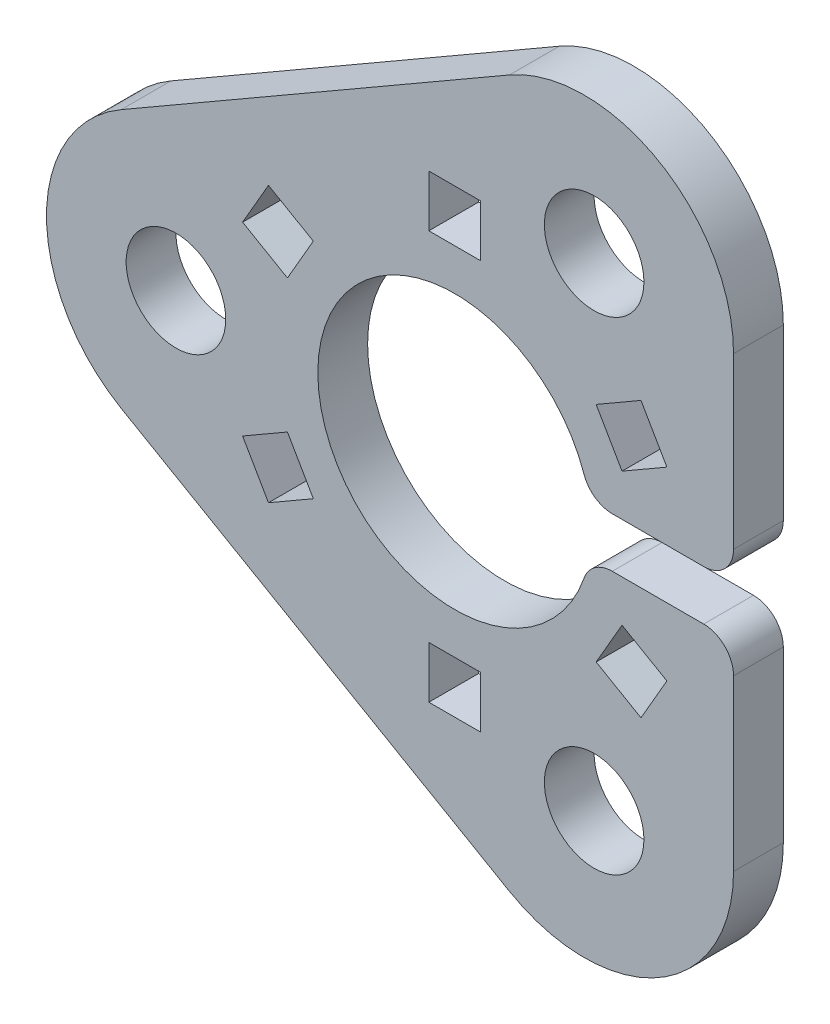
SolidWorks part; units mm, degrees
ref_plane "Front Plane" through (0, 0, 0) normal (0, 0, 1) x (1, 0, 0)
ref_plane "Top Plane" through (0, 0, 0) normal (0, 1, 0) x (1, 0, 0)
ref_plane "Right Plane" through (0, 0, 0) normal (1, 0, 0) x (0, 0, -1)
sketch "Sketch1" plane through (0, 0, 0) normal (0, 0, 1) x (1, 0, 0)
  line L0 (-26, 0) -> (26, 0) construction
  line L7 (-2.6, 23.1) -> (2.6, 23.1)
  line L8 (-2.6, 23.1) -> (-2.6, 17.9)
  line L9 (-2.6, 17.9) -> (2.6, 17.9)
  line L10 (2.6, 23.1) -> (2.6, 17.9)
  line L23 (0, 26) -> (0, -26) construction
  line L24 (21.3052, 9.2983) -> (16.8019, 6.6983)
  line L25 (14.2019, 11.2017) -> (16.8019, 6.6983)
  line L26 (18.7052, 13.8017) -> (14.2019, 11.2017)
  line L27 (18.7052, 13.8017) -> (21.3052, 9.2983)
  line L28 (18.7052, -13.8017) -> (14.2019, -11.2017)
  line L29 (16.8019, -6.6983) -> (14.2019, -11.2017)
  line L30 (21.3052, -9.2983) -> (16.8019, -6.6983)
  line L31 (21.3052, -9.2983) -> (18.7052, -13.8017)
  line L32 (-2.6, -23.1) -> (-2.6, -17.9)
  line L33 (2.6, -17.9) -> (-2.6, -17.9)
  line L34 (2.6, -23.1) -> (2.6, -17.9)
  line L35 (2.6, -23.1) -> (-2.6, -23.1)
  line L36 (-21.3052, -9.2983) -> (-16.8019, -6.6983)
  line L37 (-14.2019, -11.2017) -> (-16.8019, -6.6983)
  line L38 (-18.7052, -13.8017) -> (-14.2019, -11.2017)
  line L39 (-18.7052, -13.8017) -> (-21.3052, -9.2983)
  line L40 (-18.7052, 13.8017) -> (-14.2019, 11.2017)
  line L41 (-16.8019, 6.6983) -> (-14.2019, 11.2017)
  line L42 (-21.3052, 9.2983) -> (-16.8019, 6.6983)
  line L43 (-21.3052, 9.2983) -> (-18.7052, 13.8017)
  line L44 (28, 2.5) -> (13.5208, 2.5)
  line L45 (28, -2.5) -> (13.5208, -2.5)
  line L46 (28, 48.4974) -> (28, -48.4974) construction
  line L47 (28, -48.4974) -> (-56, 0) construction
  line L48 (-56, 0) -> (28, 48.4974) construction
  line L49 (28, 2.5) -> (28, 48.4974)
  line L50 (28, 48.4974) -> (-56, 0)
  line L51 (-56, 0) -> (28, -48.4974)
  line L52 (28, -48.4974) -> (28, -2.5)
  line L53 (0, 0) -> (28, 48.4974) construction
  line L54 (-2.6, 20.5) -> (2.6, 20.5) construction
  circle A0 centre (0, 0) radius 13.75 construction
  arc A2 (13.5208, 2.5) -> (13.5208, -2.5) centre (0, 0) ccw
  circle A4 centre (14, 24.2487) radius 5
  circle A5 centre (14, -24.2487) radius 5
  circle A6 centre (-28, 0) radius 5
  point P40 (0, 0)
  point P48 (0, 0)
  point P50 (0, 0)
  dimension "D2" = 28
  dimension "D1" = 27.5
  dimension "D10" = 10
  dimension "D3" = 5.2
  dimension "D4" = 5.2
  dimension "D5" = 20.5
  dimension "D6" = 6
  dimension "D7" = 5
  dimension "D9" = 28
  dimension "D11" = 3
  dimension "D8" = 3
extrude "Boss-Extrude1" add sketch "Sketch1" along normal blind 5
fillet "Congé1" radius 15 3 edges at (28, -48.4974, 2.5) (-56, 0, 2.5) (28, 48.4974, 2.5)
fillet "Congé2" radius 3 4 edges at (13.5208, 2.5, 2.5) (13.5208, -2.5, 2.5) (28, -2.5, 2.5) (28, 2.5, 2.5)
